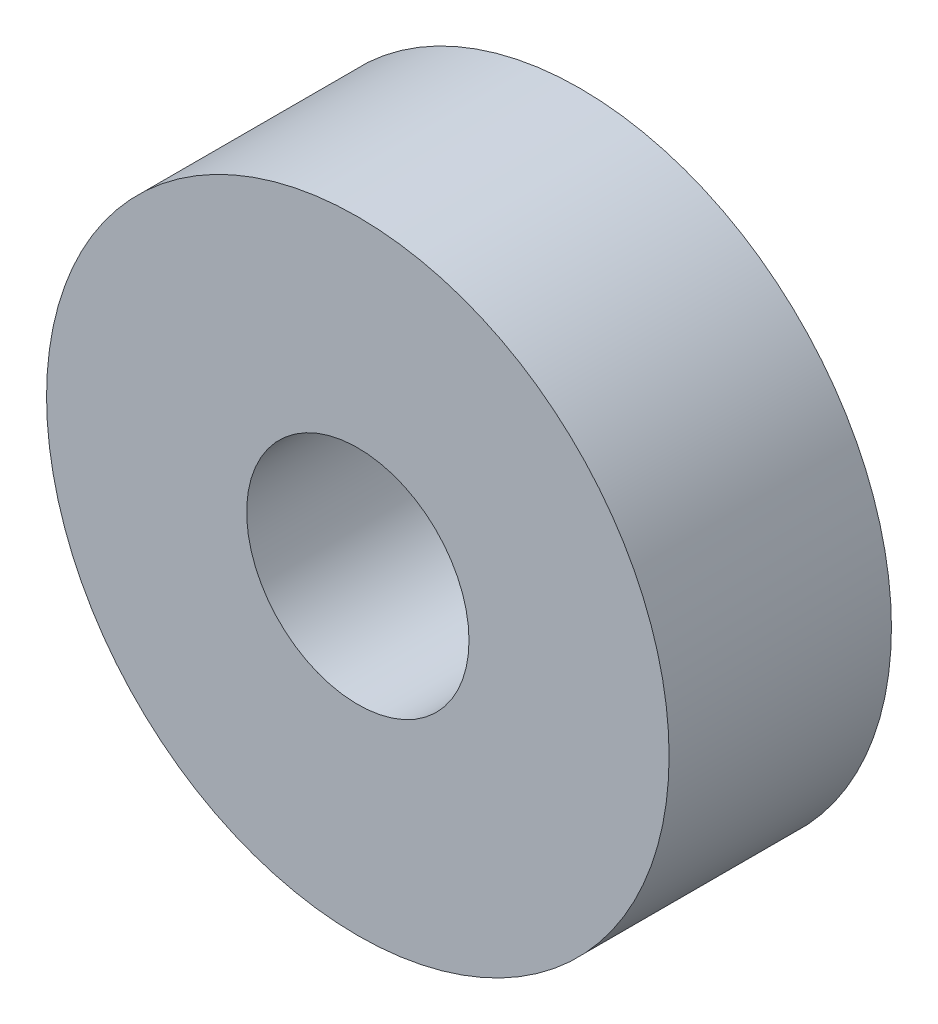
SolidWorks part; units mm, degrees
material "ASTM A36"
ref_plane "Piano frontale" through (0, 0, 0) normal (0, 0, 1) x (1, 0, 0)
ref_plane "Piano superiore" through (0, 0, 0) normal (0, 1, 0) x (1, 0, 0)
ref_plane "Piano destro" through (0, 0, 0) normal (1, 0, 0) x (0, 0, -1)
sketch "Schizzo1" plane through (0, 0, 0) normal (0, 0, 1) x (1, 0, 0)
  circle A0 centre (0, 0) radius 2.5
  circle A1 centre (0, 0) radius 7
  dimension "D1" = 5
  dimension "D2" = 14
extrude "Estrusione-Estrusione1" add sketch "Schizzo1" along normal blind 5
